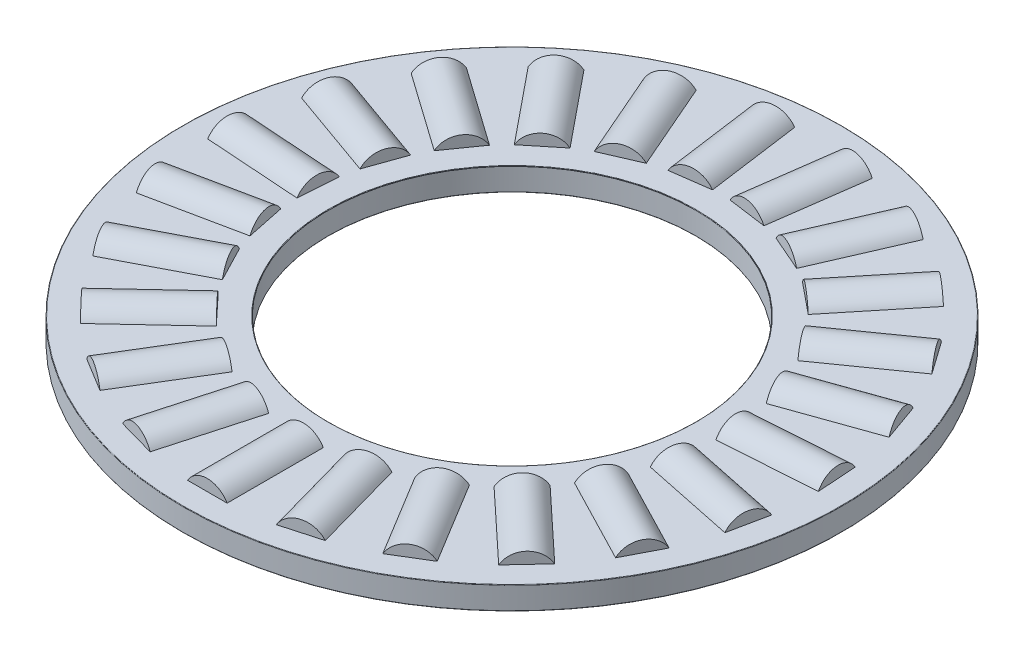
SolidWorks part; units mm, degrees
material "Alloy Steel"
ref_plane "Front Plane" through (0, 0, 0) normal (0, 0, 1) x (1, 0, 0)
ref_plane "Top Plane" through (0, 0, 0) normal (0, 1, 0) x (1, 0, 0)
ref_plane "Right Plane" through (0, 0, 0) normal (1, 0, 0) x (0, 0, -1)
sketch "Sketch1" plane through (0, 0, 0) normal (1, 0, 0) x (0, 0, -1)
  line L0 (-14.2875, 0) -> (14.2875, 0) construction
  line L1 (0, -0.9922) -> (0, 0.9922) construction
  line L2 (-14.2875, 0.4961) -> (-7.9629, 0.4961)
  line L3 (-14.2875, 0.4961) -> (-14.2875, -0.4961)
  line L4 (-14.2875, -0.4961) -> (-7.9629, -0.4961)
  line L5 (-7.9629, 0.4961) -> (-7.9629, -0.4961)
  line L7 (-11.1252, 0.9922) -> (-11.1252, 0.4961) construction
  line L8 (-13.2088, 0.9922) -> (-9.0416, 0.9922) construction
  line L9 (-13.2088, 0.9922) -> (-13.2088, -0.9922) construction
  line L10 (-13.2088, -0.9922) -> (-9.0416, -0.9922) construction
  line L11 (-9.0416, 0.9922) -> (-9.0416, -0.9922) construction
  point P16 (-13.2088, 0)
  dimension "OD" = 28.575
  dimension "Shaft Dia" = 15.9258
  dimension "Th" = 1.9844
  dimension "D2" = 0.9922
  dimension "D1" = 4.1672
  dimension "D3" = 6.3246
revolve "Revolve1" add sketch "Sketch1" angle 360 about L1
sketch "Sketch3" plane through (0, 0, 0) normal (1, 0, 0) x (0, 0, -1)
  line L0 (-13.2088, 0.9922) -> (-13.2088, -0.9922) construction
  line L1 (-13.2088, 0) -> (-9.0416, 0)
  line L2 (-13.2088, 0) -> (-13.2088, 0.9922)
  line L3 (-13.2088, 0.9922) -> (-9.0416, 0.9922)
  line L4 (-9.0416, 0) -> (-9.0416, 0.9922)
revolve "Cut-Revolve1" cut sketch "Sketch3" angle 360 about L1
sketch "Sketch2" plane through (0, 0, 0) normal (1, 0, 0) x (0, 0, -1)
  line L1 (-13.2088, 0) -> (-9.0416, 0)
  line L2 (-13.2088, 0) -> (-13.2088, 0.9922)
  line L3 (-13.2088, 0.9922) -> (-9.0416, 0.9922)
  line L4 (-9.0416, 0) -> (-9.0416, 0.9922)
revolve "Revolve2" add sketch "Sketch2" angle 360 about L1
ref_axis "Axis1" through (0, 0.9922, 0) along (0, -1, 0)
pattern_circular "CirPattern1" count 23 every 15.652 about axis through (0, 0.9922, 0) along (0, -1, 0) of bodies 187 411
pattern_circular "CirPattern2" count 23 every 15.652 about axis through (0, 0, 0) along (0, 1, 0) of "Cut-Revolve1"
sketch "Sketch4" plane through (0, 0, 0) normal (1, 0, 0) x (0, 0, -1)
  line L0 (-14.2875, 0.4961) -> (-14.2875, -0.4961) construction
  line L1 (-11.9062, 9.1091) -> (-6.35, 9.1091)
  line L2 (-11.9062, 9.1091) -> (-11.9062, 9.9219)
  line L3 (-11.9062, 9.9219) -> (-6.35, 9.9219)
  line L4 (-6.35, 9.1091) -> (-6.35, 9.9219)
  line L5 (-11.9062, -9.9219) -> (-7.9629, -9.9219)
  line L6 (-11.9062, -9.9219) -> (-11.9062, -9.1091)
  line L7 (-11.9062, -9.1091) -> (-7.9629, -9.1091)
  line L8 (-7.9629, -9.9219) -> (-7.9629, -9.1091)
  line L10 (-7.9629, 0.4961) -> (-7.9629, -0.4961) construction
  line L11 (0, 0) -> (-14.2875, 0) construction
  line L12 (-14.2875, 0) -> (14.2875, 0) construction
  line L13 (0, -0.9922) -> (0, 0.9922) construction
  dimension "Ht" = 19.8438
  dimension "Washer Th" = 0.8128
  dimension "Washer ID" = 12.7
  dimension "Washer OD" = 23.8125
fillet "Fillet2" radius 0.0198 4 edges at (0, -0.4961, -7.9629) (0, 0.4961, -7.9629) (0, -0.4961, -14.2875) (0, 0.4961, -14.2875)
equation "\"D2@Sketch1\"= \"Th@Sketch1\" * .5"
equation "\"Rollers@CirPattern1\"= \"OD@Sketch1\" * 20"
equation "\"Angle@CirPattern1\" = 360/\"Rollers@CirPattern1\""
equation "\"D1@CirPattern2\" = \"Rollers@CirPattern1\""
equation "\"D2@CirPattern2\" = \"Angle@CirPattern1\""
equation "\"Ht@Sketch4\" = \"Th@Sketch1\"*10"
